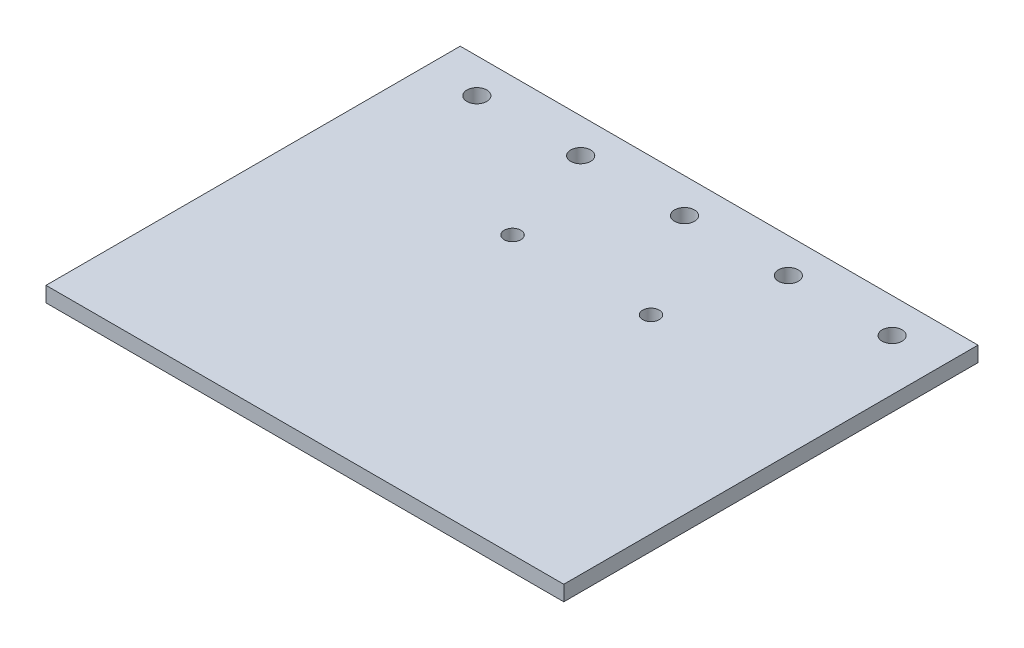
SolidWorks part; units mm, degrees
material "Acrylic (Medium-high impact)"
ref_plane "Front" through (0, 0, 0) normal (0, 0, 1) x (1, 0, 0)
ref_plane "Top" through (0, 0, 0) normal (0, 1, 0) x (1, 0, 0)
ref_plane "Right" through (0, 0, 0) normal (1, 0, 0) x (0, 0, -1)
sketch "Sketch1" plane through (0, 0, 0) normal (0, 1, 0) x (1, 0, 0)
  line L1 (-47.5, 38) -> (47.5, 38)
  line L2 (-47.5, 38) -> (-47.5, -38)
  line L3 (-47.5, -38) -> (47.5, -38)
  line L4 (47.5, 38) -> (47.5, -38)
  line L5 (-47.5, 38) -> (47.5, -38) construction
  line L6 (-47.5, -38) -> (47.5, 38) construction
  point P0 (0, 0)
  dimension "D1" = 95
  dimension "D2" = 76
extrude "Boss-Extrude1" add sketch "Sketch1" along normal blind 2.794
sketch "Sketch2" plane through (0, 2.794, 0) normal (0, 1, 0) x (1, 0, 0)
  line L0 (0, 0) -> (0, 38) construction
  line L1 (47.5, 38) -> (-47.5, 38) construction
  line L2 (-38.1, 31.65) -> (0, 31.65) construction
  line L3 (0, 31.65) -> (38.1, 31.65) construction
  circle A0 centre (-38.1, 31.65) radius 1.8288
  circle A1 centre (-19.05, 31.65) radius 1.8288
  circle A2 centre (0, 31.65) radius 1.8288
  circle A3 centre (19.05, 31.65) radius 1.8288
  circle A4 centre (38.1, 31.65) radius 1.8288
  dimension "D3" = 3.6576
  dimension "D1" = 76.2
  dimension "D2" = 6.35
extrude "Cut-Extrude1" cut sketch "Sketch2" against normal through all
sketch "Sketch3" plane through (0, 2.794, 0) normal (0, 1, 0) x (1, 0, 0)
  line L0 (0, -38) -> (0, 12.8) construction
  line L1 (-47.5, -38) -> (47.5, -38) construction
  line L2 (-12.7, 12.8) -> (12.7, 12.8) construction
  circle A0 centre (-12.7, 12.8) radius 1.524
  circle A1 centre (12.7, 12.8) radius 1.524
  dimension "D3" = 3.048
  dimension "D1" = 25.4
  dimension "D2" = 50.8
extrude "Cut-Extrude2" cut sketch "Sketch3" against normal through all
